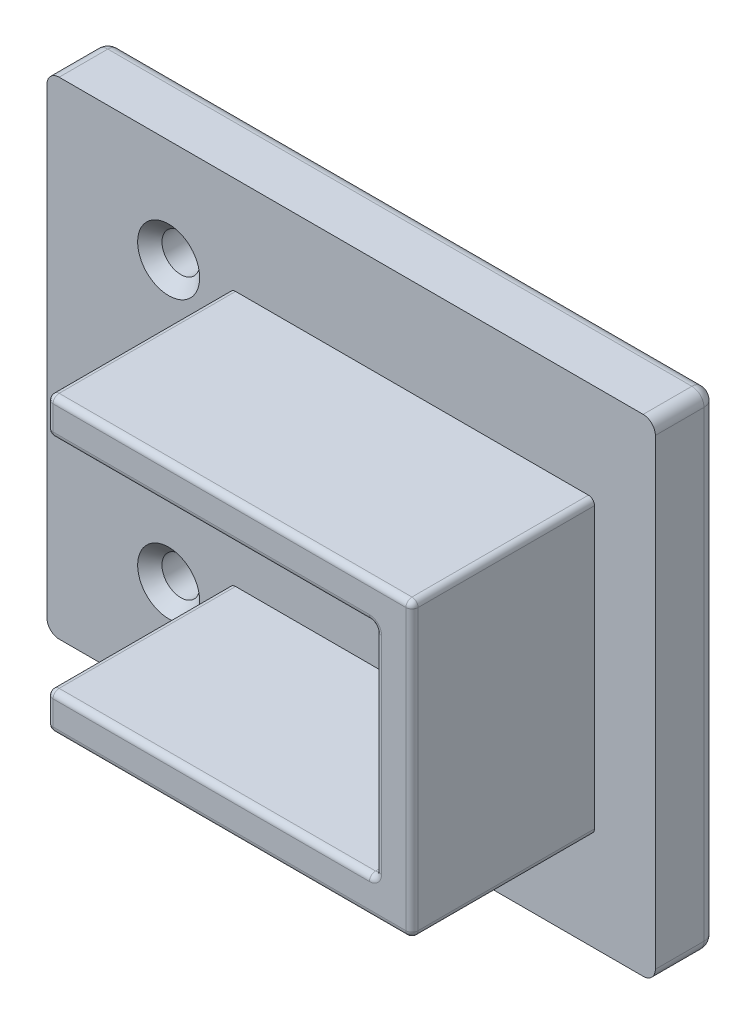
SolidWorks part; units mm, degrees
ref_plane "前视基准面" through (0, 0, 0) normal (0, 0, 1) x (1, 0, 0)
ref_plane "上视基准面" through (0, 0, 0) normal (0, 1, 0) x (1, 0, 0)
ref_plane "右视基准面" through (0, 0, 0) normal (1, 0, 0) x (0, 0, -1)
other "Configuration Table"
sketch "草图2" plane through (0, 0, 0) normal (0, 0, 1) x (1, 0, 0)
  line L1 (25, 20) -> (-25, 20)
  line L2 (25, 20) -> (25, -20)
  line L3 (25, -20) -> (-25, -20)
  line L4 (-25, 20) -> (-25, -20)
  line L5 (88, 0) -> (-32, 0) construction
  dimension "D1" = 40
  dimension "D2" = 50
  dimension "D3" = 25
extrude "凸台-拉伸1" add sketch "草图2" along normal blind 5
sketch "草图5" plane through (0, -20, 0) normal (0, -1, 0) x (1, 0, 0)
  line L0 (20, 5) -> (20, 20)
  line L1 (-25, 5) -> (25, 5) construction
  line L2 (20, 20) -> (-10, 20)
  line L3 (-10, 20) -> (-10, 5)
  line L4 (-10, 5) -> (20, 5)
  line L5 (25, 5) -> (25, 0) construction
  dimension "D1" = 30
  dimension "D2" = 15
  dimension "D4" = 5
extrude "凸台-拉伸2" add sketch "草图5" against normal blind 3 from offset 8 offset against normal yes
sketch "草图6" plane through (0, 20, 0) normal (0, 1, 0) x (1, 0, 0)
  line L4 (20, -20) -> (20, -5)
  line L5 (-10, -20) -> (20, -20)
  line L6 (-10, -5) -> (-10, -20)
  line L7 (20, -5) -> (-10, -5)
  line L8 (20, -20) -> (20, -5)
  line L9 (-10, -20) -> (20, -20)
  line L10 (-10, -5) -> (-10, -20)
  line L11 (20, -5) -> (-10, -5)
  dimension "D1" = 0
extrude "凸台-拉伸3" add sketch "草图6" against normal blind 3 from offset 8 offset against normal yes
sketch "草图7" plane through (0, 0, 0) normal (0, 0, -1) x (-1, 0, 0)
  line L0 (0, 0) -> (-49464.6492, 0) construction
  circle A4 centre (-10, 0) radius 1.55
  circle A5 centre (15, -11.5) radius 1.55
  circle A6 centre (15, 11.5) radius 1.55
  dimension "D1" = 3.1
  dimension "D2" = 25
  dimension "D3" = 11.5
  dimension "D4" = 11.5
  dimension "D5" = 10
extrude "切除-拉伸1" cut sketch "草图7" against normal up to next
sketch "草图8" plane through (20, 0, 0) normal (1, 0, 0) x (0, 0, -1)
  line L1 (-20, 9) -> (-5, 9)
  line L2 (-20, 9) -> (-20, -12)
  line L3 (-20, -12) -> (-5, -12)
  line L4 (-5, 9) -> (-5, -12)
extrude "凸台-拉伸4" add sketch "草图8" against normal blind 3
fillet "圆角4" radius 0.5 16 edges at (3.5, 9, 20) (-10, 10.5, 20) (5, 12, 20) (20, 0, 20) (5, -12, 20) (-10, -10.5, 20) (3.5, -9, 20) (17, 0, 20) (17, -9, 12.5) (-10, -9, 12.5) (-10, -12, 12.5) (20, 12, 12.5) (-10, 12, 12.5) (-10, 9, 12.5) (17, 9, 12.5) (20, -12, 12.5)
chamfer "倒角1" distance 1 angle 45 6 edges at (-16.55, 11.5, 5) (-16.55, 11.5, 0) (-16.55, -11.5, 5) (-16.55, -11.5, 0) (8.45, 0, 5) (8.45, 0, 0)
fillet "圆角3" radius 1 11 edges at (-25, -20, 2.5) (-25, 20, 2.5) (25, 20, 2.5) (25, -20, 2.5) (0, 20, 0) (-25, 0, 0) (0, -20, 0) (25, 0, 0) (7.45, 0, 0) (-17.55, -11.5, 0) (-17.55, 11.5, 0)
